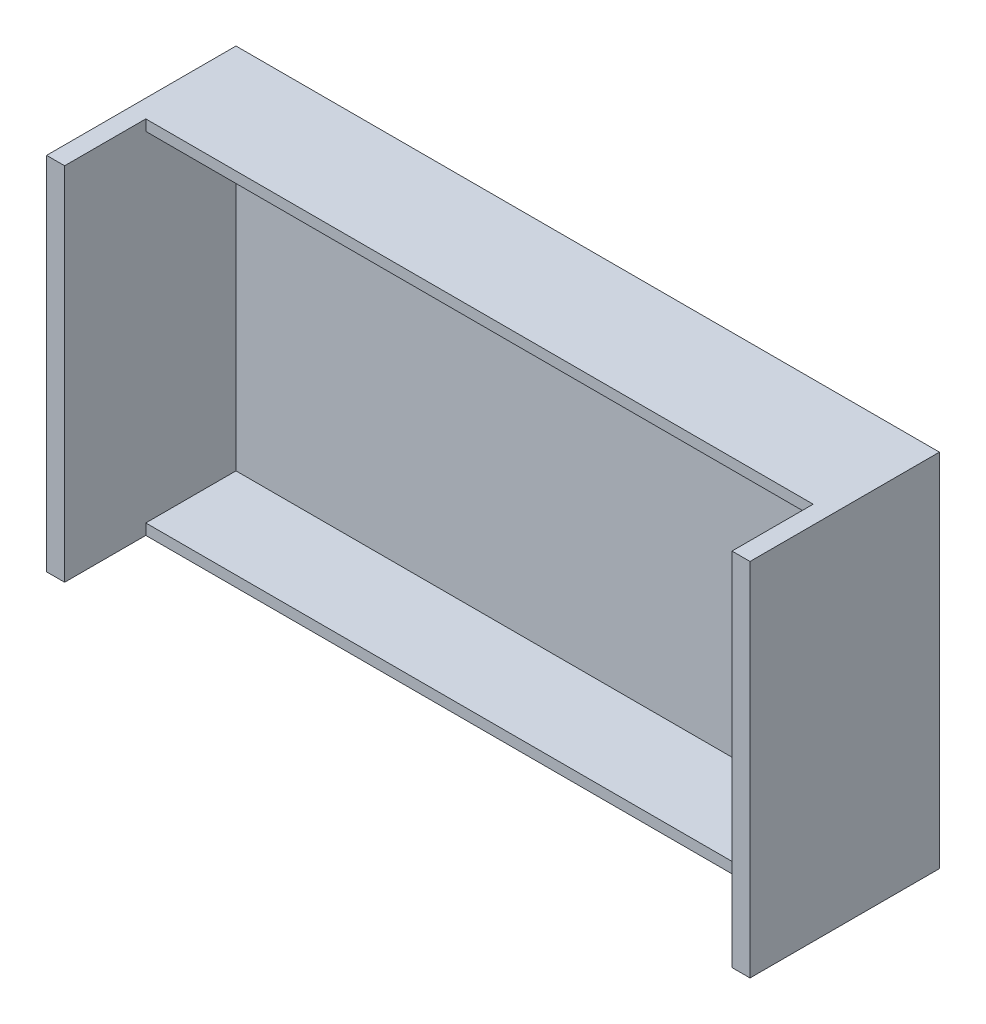
SolidWorks part; units mm, degrees
ref_plane "Front Plane" through (0, 0, 0) normal (0, 0, 1) x (1, 0, 0)
ref_plane "Top Plane" through (0, 0, 0) normal (0, 1, 0) x (1, 0, 0)
ref_plane "Right Plane" through (0, 0, 0) normal (1, 0, 0) x (0, 0, -1)
ref_plane "Plane1" through (0, 0, 3) normal (0, 0, 1) x (1, 0, 0)
sketch "Sketch1" plane through (0, 0, 3) normal (0, 0, 1) x (1, 0, 0)
  line L1 (-39, -60) -> (39, -60)
  line L2 (-39, -60) -> (-39, -20)
  line L3 (-39, -20) -> (39, -20)
  line L4 (39, -60) -> (39, -20)
  line L5 (-39, -60) -> (39, -20) construction
  line L6 (-39, -20) -> (39, -60) construction
  point P0 (0, -40)
extrude "Boss-Extrude1" add sketch "Sketch1" along normal blind 2
sketch "Sketch2" plane through (0, 0, 3) normal (0, 0, 1) x (1, 0, 0)
  line L0 (39, -20) -> (-39, -20) construction
  line L1 (-39, -60) -> (-37, -60)
  line L2 (-39, -60) -> (-39, -20)
  line L3 (-39, -20) -> (-37, -20)
  line L4 (-37, -60) -> (-37, -20)
  line L5 (-39, -60) -> (-37, -20) construction
  line L6 (-39, -20) -> (-37, -60) construction
  point P0 (-38, -40)
extrude "Boss-Extrude2" add sketch "Sketch2" along normal blind 21
sketch "Sketch3" plane through (0, 0, 3) normal (0, 0, 1) x (1, 0, 0)
  line L1 (37, -60) -> (39, -60)
  line L2 (37, -60) -> (37, -20)
  line L3 (37, -20) -> (39, -20)
  line L4 (39, -60) -> (39, -20)
  line L5 (37, -60) -> (39, -20) construction
  line L6 (37, -20) -> (39, -60) construction
  point P0 (38, -40)
extrude "Boss-Extrude3" add sketch "Sketch3" along normal blind 21
sketch "Sketch4" plane through (0, 0, 3) normal (0, 0, 1) x (1, 0, 0)
  line L0 (37, -20) -> (37, -60) construction
  line L1 (-37, -60) -> (37, -60)
  line L2 (-37, -60) -> (-37, -58.8)
  line L3 (-37, -58.8) -> (37, -58.8)
  line L4 (37, -60) -> (37, -58.8)
  line L5 (-37, -60) -> (37, -58.8) construction
  line L6 (-37, -58.8) -> (37, -60) construction
  point P0 (0, -59.4)
extrude "Boss-Extrude4" add sketch "Sketch4" along normal blind 12
sketch "Sketch5" plane through (0, 0, 3) normal (0, 0, 1) x (1, 0, 0)
  line L1 (-37, -21.2) -> (37, -21.2)
  line L2 (-37, -21.2) -> (-37, -20)
  line L3 (-37, -20) -> (37, -20)
  line L4 (37, -21.2) -> (37, -20)
  line L5 (-37, -21.2) -> (37, -20) construction
  line L6 (-37, -20) -> (37, -21.2) construction
  point P0 (0, -20.6)
extrude "Boss-Extrude5" add sketch "Sketch5" along normal blind 12
